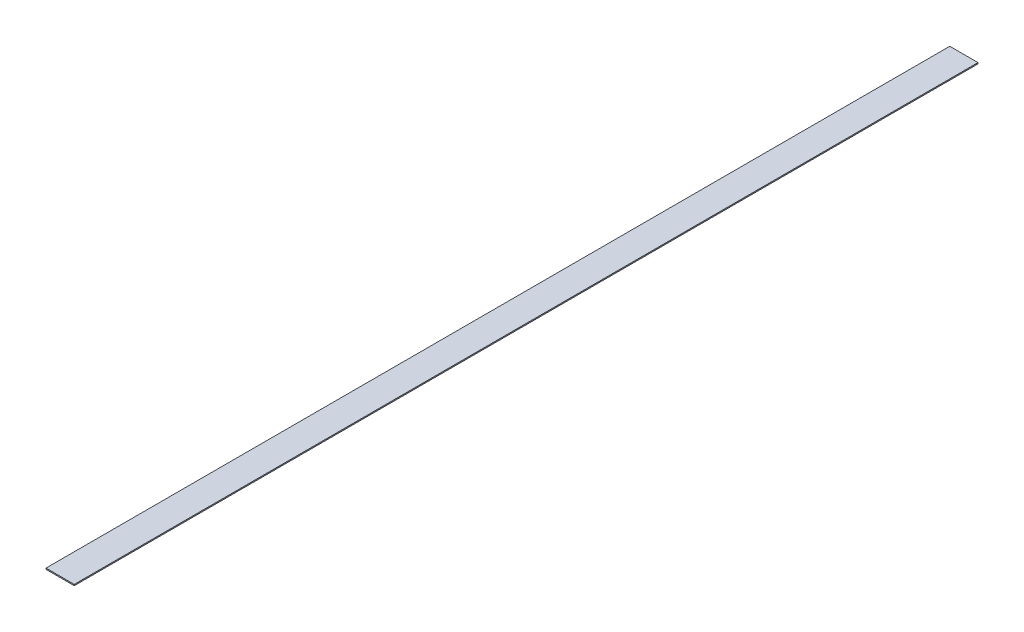
SolidWorks part; units mm, degrees
ref_plane "Front" through (0, 0, 0) normal (0, 0, 1) x (1, 0, 0)
ref_plane "Top" through (0, 0, 0) normal (0, 1, 0) x (1, 0, 0)
ref_plane "Right" through (0, 0, 0) normal (1, 0, 0) x (0, 0, -1)
sketch "Sketch1" plane through (0, 0, 0) normal (0, 1, 0) x (1, 0, 0)
  line L0 (-9.525, 304.8) -> (9.525, -304.8) construction
  line L1 (-9.525, 304.8) -> (9.525, 304.8)
  line L2 (-9.525, 304.8) -> (-9.525, -304.8)
  line L3 (-9.525, -304.8) -> (9.525, -304.8)
  line L4 (9.525, 304.8) -> (9.525, -304.8)
  line L5 (0, 0) -> (0, -75.9549) construction
  point P4 (0, 0)
  dimension "D1" = 19.05
  dimension "D2" = 609.6
extrude "Extrude1" add sketch "Sketch1" along normal blind 0.7937
